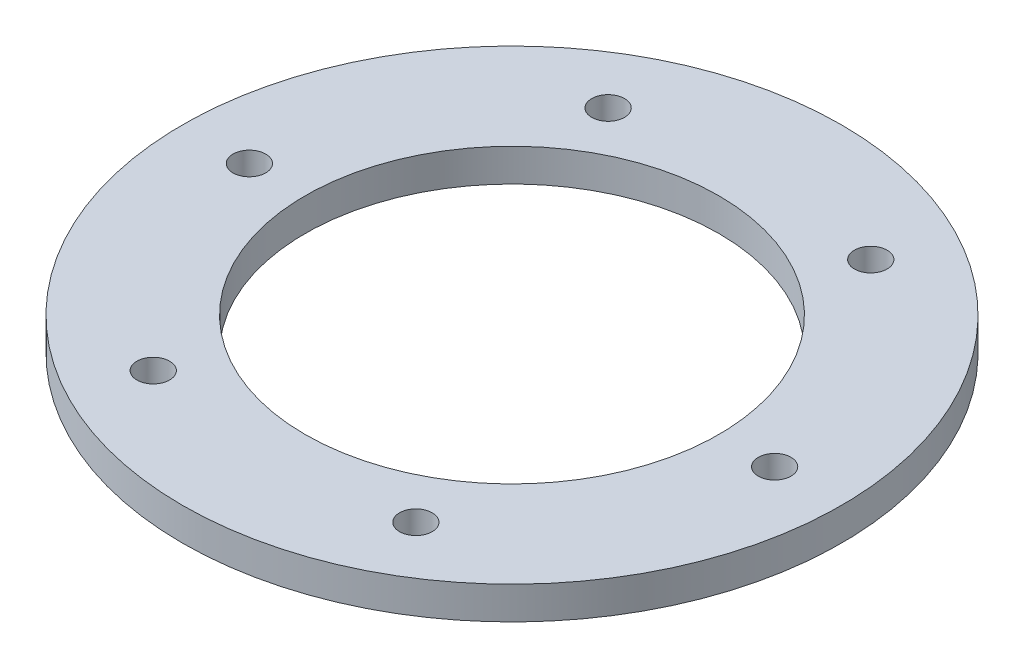
SolidWorks part; units mm, degrees
material "Thornel Mat VMA"
ref_plane "前视基准面" through (0, 0, 0) normal (0, 0, 1) x (1, 0, 0)
ref_plane "上视基准面" through (0, 0, 0) normal (0, 1, 0) x (1, 0, 0)
ref_plane "右视基准面" through (0, 0, 0) normal (1, 0, 0) x (0, 0, -1)
other "Configuration Table"
sketch "草图1" plane through (0, 0, 0) normal (0, 0, 1) x (1, 0, 0)
  line L0 (0, 0) -> (0, 10.3726) construction
  line L1 (40.28, 4) -> (25.28, 4)
  line L5 (40.28, 0) -> (40.28, 4)
  line L6 (25.28, 4) -> (25.28, 0)
  line L7 (25.28, 0) -> (40.28, 0)
  dimension "D1" = 40.28
  dimension "D2" = 4
  dimension "D3" = 15
revolve "旋转1" add sketch "草图1" angle 360 about L0
sketch "草图2" plane through (0, 4, 0) normal (0, 1, 0) x (1, 0, 0)
  circle A0 centre (0, 0) radius 32.1 construction
  circle A1 centre (-32.1, 0) radius 2
  circle A2 centre (-16.05, 27.7994) radius 2
  circle A3 centre (16.05, 27.7994) radius 2
  circle A4 centre (32.1, 0) radius 2
  circle A5 centre (16.05, -27.7994) radius 2
  circle A6 centre (-16.05, -27.7994) radius 2
  point P18 (0, 0)
  dimension "D1" = 64.2
  dimension "D2" = 4
  dimension "D3" = 6
extrude "切除-拉伸1" cut sketch "草图2" against normal blind 10
